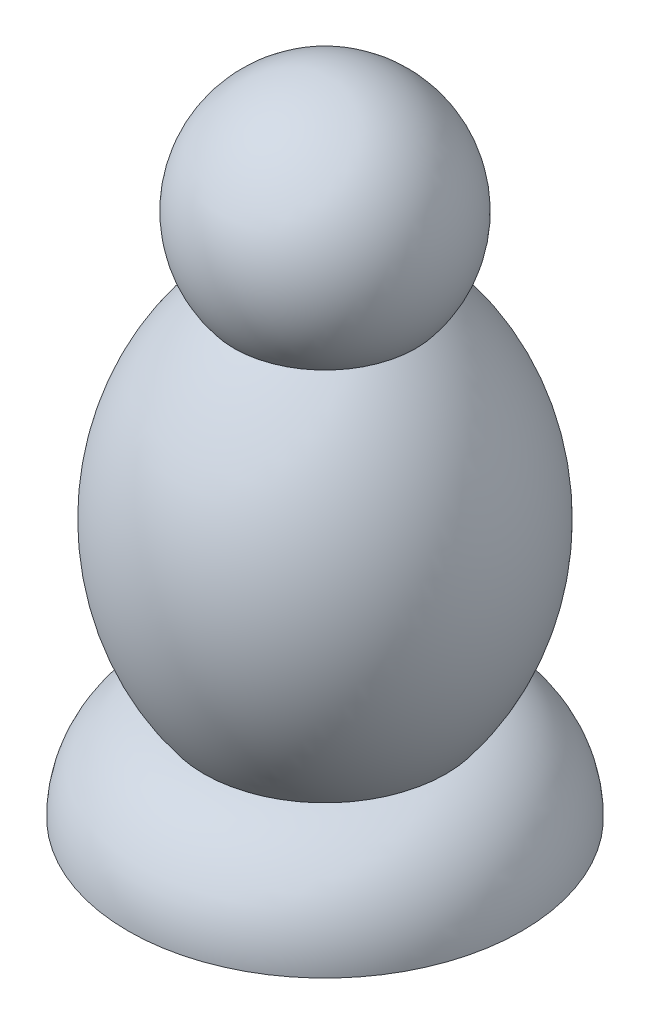
SolidWorks part; units mm, degrees
material "Ductile Iron"
ref_plane "Front Plane" through (0, 0, 0) normal (0, 0, 1) x (1, 0, 0)
ref_plane "Top Plane" through (0, 0, 0) normal (0, 1, 0) x (1, 0, 0)
ref_plane "Right Plane" through (0, 0, 0) normal (1, 0, 0) x (0, 0, -1)
sketch "Sketch1" plane through (0, 0, 0) normal (0, 0, 1) x (1, 0, 0)
  line L0 (0, -23.5851) -> (0, 59.8172) construction
  line L1 (0, 0) -> (7.5, 0)
  line L2 (0, 0) -> (0, 24.4514)
  arc A2 (3.4688, 17.2103) -> (0, 24.4514) centre (0, 20) ccw
  arc A3 (7.5, 0) -> (4.6118, 3.7407) centre (3.6335, 0) ccw
  arc A4 (4.6118, 3.7407) -> (3.4688, 17.2103) centre (-3.4407, 9.8407) ccw
  dimension "D2" = 20
  dimension "D1" = 7.5
revolve "Revolve1" add sketch "Sketch1" angle 360 about L0
